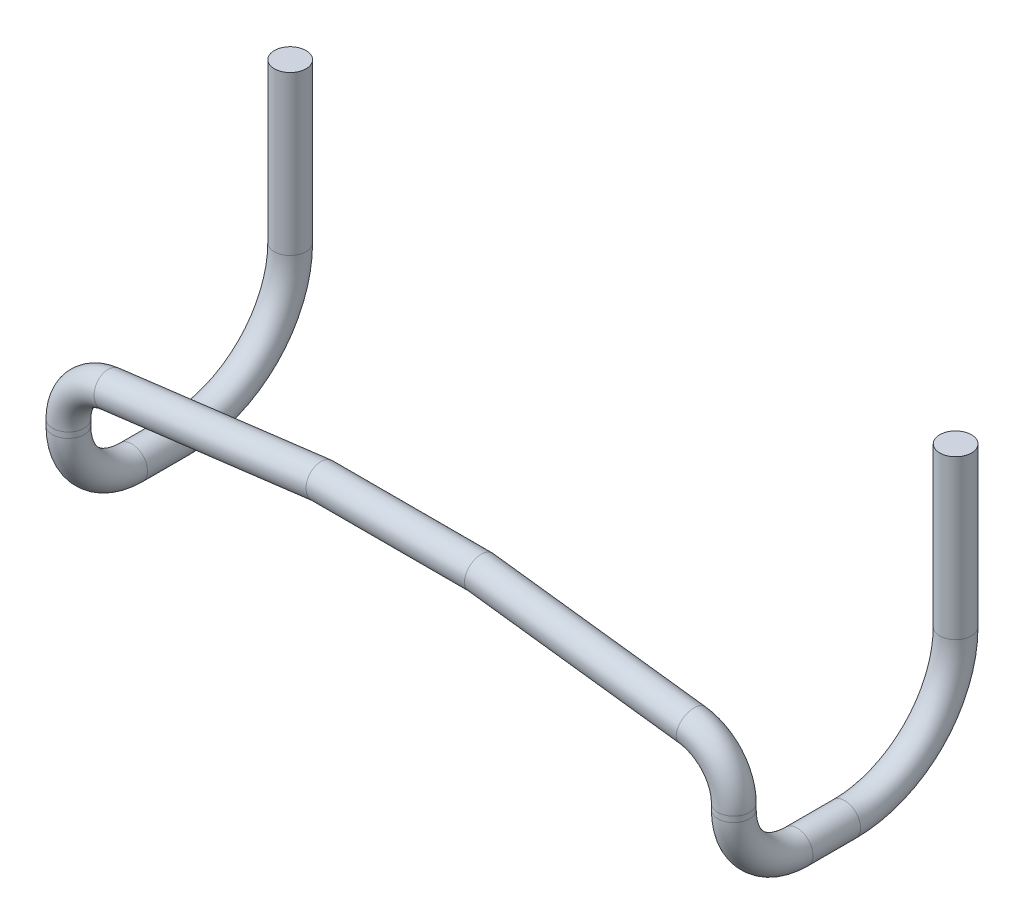
SolidWorks part; units mm, degrees
ref_plane "Front Plane" through (0, 0, 0) normal (0, 0, 1) x (1, 0, 0)
ref_plane "Top Plane" through (0, 0, 0) normal (0, 1, 0) x (1, 0, 0)
ref_plane "Right Plane" through (0, 0, 0) normal (1, 0, 0) x (0, 0, -1)
sketch3d "3DSketch2"
  line L0 (0, 0, 0) -> (50, 0, 0)
  line L1 (50, 0, 0) -> (183.721, -16.7151, 0)
  line L2 (0, 0, 0) -> (0, -20, 0) construction
  line L3 (0, -20, 0) -> (210, -20, 0) construction
  line L4 (210, -46.4835, 0) -> (210, -50, 0)
  line L5 (210, -90, -40) -> (210, -90, -70)
  line L6 (210, -20, -140) -> (210, 80, -140)
  arc A0 (210, -50, 0) -> (210, -90, -40) centre (210, -50, -40) ccw
  arc A1 (183.721, -16.7151, 0) -> (210, -46.4835, 0) centre (180, -46.4835, 0) ccw
  arc A2 (210, -90, -70) -> (210, -20, -140) centre (210, -20, -70) ccw
  point P10 (210, -90, 0)
  point P11 (250, -50, -40)
  point P14 (210, -20, 0)
  point P16 (180, -46.4835, -30)
  point P19 (210, -90, -140)
  point P20 (280, -20, -70)
  dimension "D7" = 40
  dimension "D8" = 30
  dimension "D9" = 70
  dimension "D1" = 20
  dimension "D2" = 210
  dimension "D3" = 50
  dimension "D4" = 70
  dimension "D5" = 140
  dimension "D6" = 170
sweep "Sweep1" add path "3DSketch2" circular profile diameter 20 parameters "D3"=20
mirror "Mirror1" about plane through (0, 0, 0) normal (-1, 0, 0) of "Sweep1"
